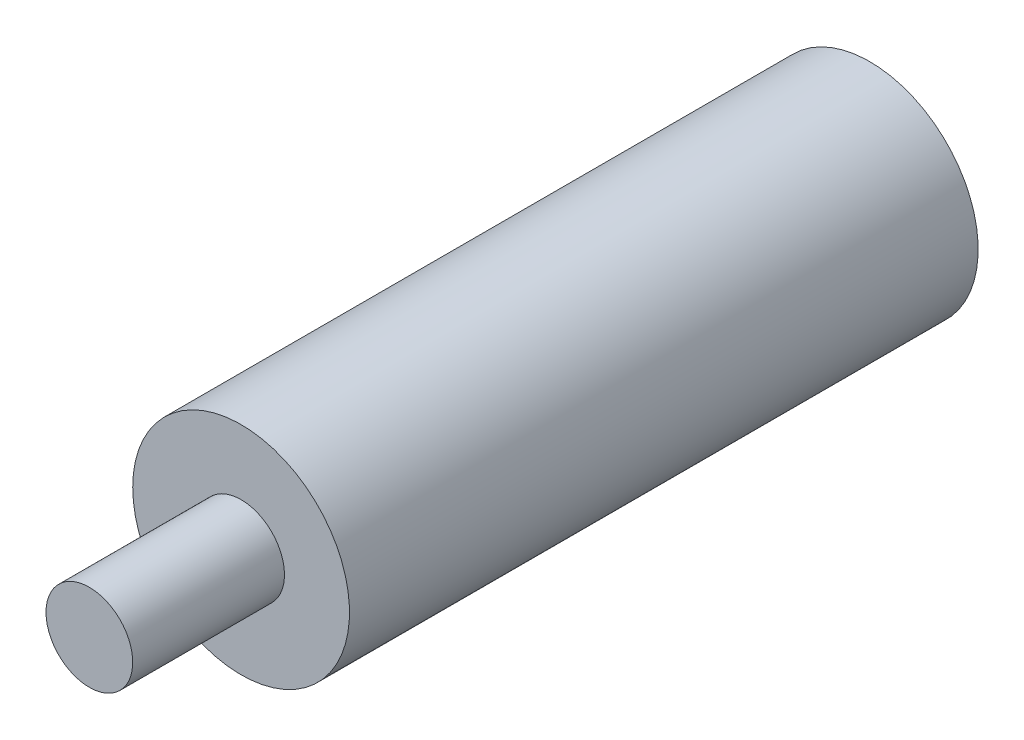
SolidWorks part; units mm, degrees
ref_plane "Front Plane" through (0, 0, 0) normal (0, 0, 1) x (1, 0, 0)
ref_plane "Top Plane" through (0, 0, 0) normal (0, 1, 0) x (1, 0, 0)
ref_plane "Right Plane" through (0, 0, 0) normal (1, 0, 0) x (0, 0, -1)
sketch "Sketch1" plane through (0, 0, 0) normal (1, 0, 0) x (0, 0, -1)
  line L0 (0, 0) -> (0, 10)
  line L1 (0, 10) -> (35, 10)
  line L2 (35, 10) -> (35, 25)
  line L3 (35, 25) -> (180, 25)
  line L4 (180, 25) -> (180, 0)
  line L5 (145, 0) -> (0, 0) construction
  line L6 (0, 0) -> (180, 0)
  dimension "D1" = 180
  dimension "D2" = 35
  dimension "D3" = 145
  dimension "D4" = 50
  dimension "D5" = 20
revolve "Revolve1" add sketch "Sketch1" angle 360 about L5
